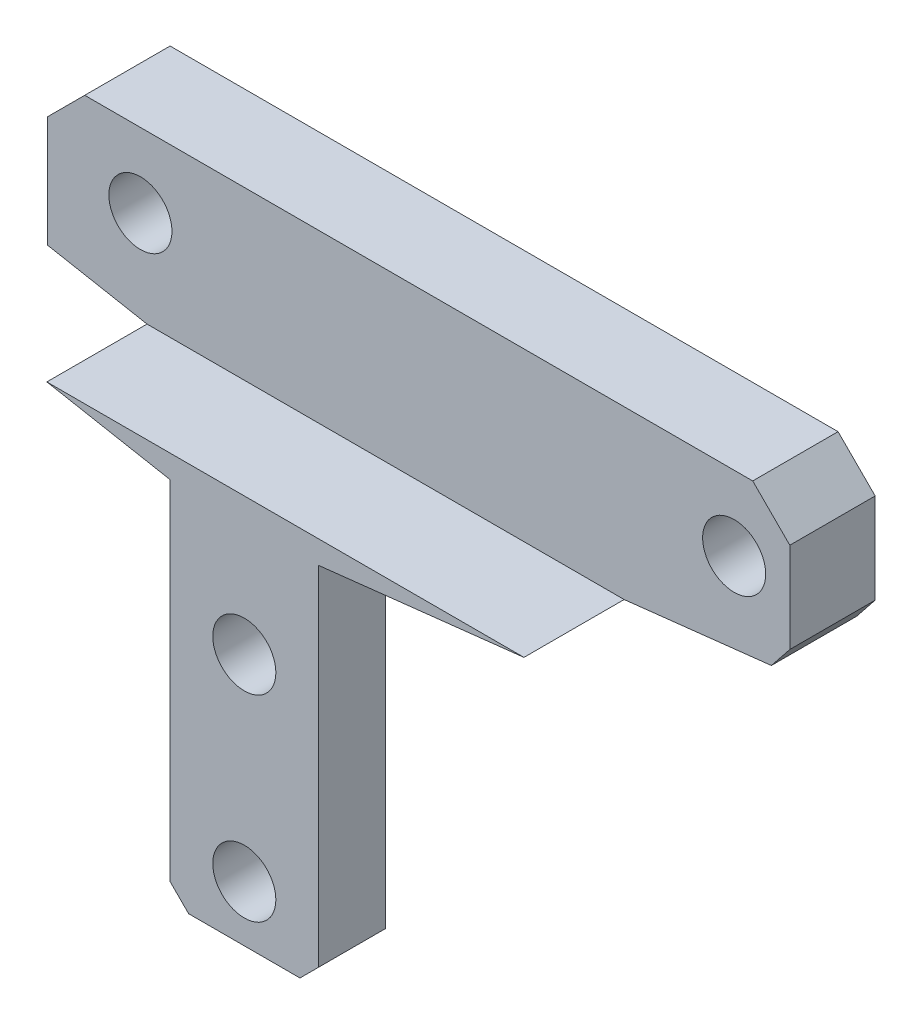
SolidWorks part; units mm, degrees
ref_plane "前视基准面" through (0, 0, 0) normal (0, 0, 1) x (1, 0, 0)
ref_plane "上视基准面" through (0, 0, 0) normal (0, 1, 0) x (1, 0, 0)
ref_plane "右视基准面" through (0, 0, 0) normal (1, 0, 0) x (0, 0, -1)
other "Configuration Table"
sketch "草图1" plane through (0, 0, 0) normal (0, 0, 1) x (1, 0, 0)
  line L1 (-10, 2) -> (10, 2)
  line L2 (-10, 2) -> (-10, -2)
  line L4 (10, 2) -> (10, -2)
  line L5 (-10, 2) -> (10, -2) construction
  line L6 (-10, -2) -> (10, 2) construction
  line L8 (-4, -3.12) -> (-4, -13)
  line L9 (-4, -13) -> (0, -13)
  line L10 (0, -3.12) -> (0, -13)
  line L11 (-10, -2) -> (-4, -3.12)
  line L12 (0, -3.12) -> (10, -2)
  circle A0 centre (-7.5, 0) radius 0.85
  circle A1 centre (8.5, 0) radius 0.85
  circle A2 centre (-2, -11.5) radius 0.85
  circle A3 centre (-2, -6.2) radius 0.85
  point P0 (0, 0)
  dimension "D5" = 9.88
  dimension "D7" = 1.12
  dimension "D13" = 1.7
  dimension "D1" = 20
  dimension "D2" = 4
  dimension "D3" = 4
  dimension "D4" = 1.12
  dimension "D6" = 2.5
  dimension "D8" = 1.5
  dimension "D9" = 10
  dimension "D10" = 2
  dimension "D11" = 2
  dimension "D14" = 2
  dimension "D15" = 2
  dimension "D16" = 1.5
  dimension "D17" = 5.3
extrude "凸台-拉伸2" add sketch "草图1" along normal blind 5.5
sketch "草图3" plane through (0, 0, 0) normal (0, 0, -1) x (-1, 0, 0)
  line L0 (0, -3.12) -> (4, -3.12)
  line L8 (-10, 2) -> (-10, -2)
  line L9 (-10, -2) -> (0, -3.12)
  line L10 (0, -3.12) -> (0, -13)
  line L11 (0, -13) -> (4, -13)
  line L12 (4, -13) -> (4, -3.12)
  line L14 (10, -2) -> (10, 2)
  line L15 (10, 2) -> (-10, 2)
  line L18 (0, -3.12) -> (0, -13)
  line L19 (0, -13) -> (4, -13)
  line L20 (4, -13) -> (4, -3.12)
  line L25 (4, -3.12) -> (10, -2)
  circle A0 centre (2, -11.5) radius 0.85 construction
  circle A1 centre (2, -6.2) radius 0.85 construction
  circle A2 centre (2, -11.5) radius 0.85
  circle A3 centre (2, -6.2) radius 0.85
  dimension "D2" = 0
  dimension "D1" = 0
extrude "切除-拉伸2" cut sketch "草图3" against normal blind 4.2
chamfer "倒角1" distance 1 angle 45 1 edges at (-2, -3.12, 4.2)
chamfer "倒角2" distance 1 angle 45 2 edges at (-10, 2, 2.75) (10, 2, 2.75)
chamfer "倒角3" distance 0.5 angle 45 2 edges at (-4, -13, 4.85) (0, -13, 4.85)
sketch "草图4" plane through (0, 0, 5.5) normal (0, 0, 1) x (1, 0, 0)
  line L6 (-10, -2.5) -> (10, -2.5)
  line L12 (-4, -3.12) -> (-4, -12.5)
  line L13 (-4, -12.5) -> (-3.5, -13)
  line L14 (-3.5, -13) -> (-0.5, -13)
  line L15 (-0.5, -13) -> (0, -12.5)
  line L16 (0, -12.5) -> (0, -3.12)
  line L17 (0, -3.12) -> (10, -2)
  line L18 (10, -2) -> (10, 1)
  line L19 (10, 1) -> (9, 2)
  line L20 (9, 2) -> (-9, 2)
  line L21 (-9, 2) -> (-10, 1)
  line L22 (-10, 1) -> (-10, -2)
  line L23 (-10, -2) -> (-4, -3.12)
  line L30 (10, -2.5) -> (10, 1)
  line L31 (10, 1) -> (9, 2)
  line L32 (9, 2) -> (-9, 2)
  line L33 (-9, 2) -> (-10, 1)
  line L34 (-10, 1) -> (-10, -2.5)
  circle A0 centre (8.5, 0) radius 0.85 construction
  circle A1 centre (-7.5, 0) radius 0.85 construction
  circle A2 centre (8.5, 0) radius 0.85
  circle A3 centre (-7.5, 0) radius 0.85
  dimension "D2" = 4.5
  dimension "D1" = 0
extrude "切除-拉伸3" cut sketch "草图4" against normal blind 2.2
chamfer "倒角4" distance 0.5 angle 45 1 edges at (10, -2, 1.65)
sketch "草图5" plane through (0, 0, 0) normal (0, 0, -1) x (-1, 0, 0)
  line L11 (-10, 1) -> (-10, -1.4334)
  line L12 (-10, -1.4334) -> (-9.5031, -2.0557)
  line L13 (-9.5031, -2.0557) -> (0, -3.12)
  line L15 (0, -3.12) -> (4, -3.12)
  line L17 (4, -3.12) -> (10, -2)
  line L18 (10, -2) -> (10, 1)
  line L19 (10, 1) -> (9, 2)
  line L20 (9, 2) -> (-9, 2)
  line L21 (-9, 2) -> (-10, 1)
  line L22 (-10, 1) -> (-10, -1.4334)
  line L23 (-10, -1.4334) -> (-9.5031, -2.0557)
  line L24 (-9.5031, -2.0557) -> (0, -3.12)
  line L26 (0, -3.12) -> (4, -3.12)
  line L28 (4, -3.12) -> (10, -2)
  line L29 (10, -2) -> (10, 1)
  line L30 (10, 1) -> (9, 2)
  line L31 (9, 2) -> (-9, 2)
  line L32 (-9, 2) -> (-10, 1)
  circle A0 centre (7.5, 0) radius 0.85 construction
  circle A1 centre (-8.5, 0) radius 0.85 construction
  circle A2 centre (7.5, 0) radius 0.85
  circle A3 centre (-8.5, 0) radius 0.85
  dimension "D1" = 0
extrude "切除-拉伸4" cut sketch "草图5" against normal blind 1
sketch "草图6" plane through (0, 0, 5.5) normal (0, 0, 1) x (1, 0, 0)
  line L8 (0, -3.12) -> (5.5357, -2.5)
  line L9 (5.5357, -2.5) -> (-7.3214, -2.5)
  line L10 (-7.3214, -2.5) -> (-4, -3.12)
  line L11 (-4, -3.12) -> (-4, -12.5)
  line L12 (-4, -12.5) -> (-3.5, -13)
  line L13 (-3.5, -13) -> (-0.5, -13)
  line L14 (-0.5, -13) -> (0, -12.5)
  line L15 (0, -12.5) -> (0, -3.12)
  line L16 (0, -3.12) -> (5.5357, -2.5)
  line L17 (5.5357, -2.5) -> (-7.3214, -2.5)
  line L18 (-7.3214, -2.5) -> (-4, -3.12)
  line L19 (-4, -3.12) -> (-4, -12.5)
  line L20 (-4, -12.5) -> (-3.5, -13)
  line L21 (-3.5, -13) -> (-0.5, -13)
  line L22 (-0.5, -13) -> (0, -12.5)
  line L23 (0, -12.5) -> (0, -3.12)
  circle A0 centre (-2, -11.5) radius 0.85 construction
  circle A1 centre (-2, -6.2) radius 0.85 construction
  circle A2 centre (-2, -11.5) radius 0.85
  circle A3 centre (-2, -6.2) radius 0.85
  dimension "D1" = 0
extrude "凸台-拉伸3" add sketch "草图6" along normal blind 0.5
